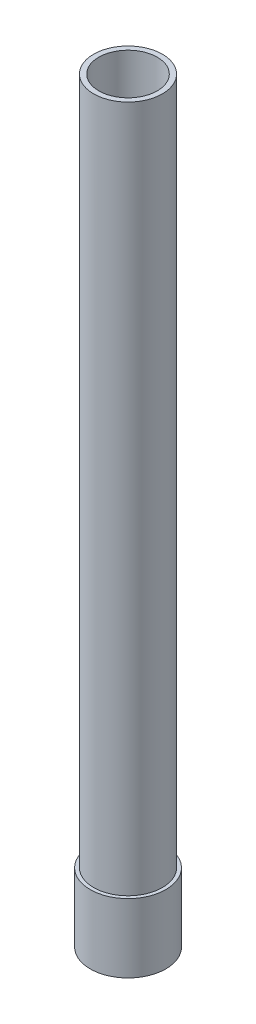
SolidWorks part; units mm, degrees
ref_plane "Front Plane" through (0, 0, 0) normal (0, 0, 1) x (1, 0, 0)
ref_plane "Top Plane" through (0, 0, 0) normal (0, 1, 0) x (1, 0, 0)
ref_plane "Right Plane" through (0, 0, 0) normal (1, 0, 0) x (0, 0, -1)
sketch "Sketch1" plane through (0, 0, 0) normal (0, 1, 0) x (1, 0, 0)
  circle A0 centre (0, 0) radius 10
  dimension "D1" = 20
extrude "Boss-Extrude1" add sketch "Sketch1" along normal blind 200
shell "Shell1" thickness 1.5
sketch "Sketch2" plane through (0, 0, 0) normal (0, -1, 0) x (1, 0, 0)
  circle A0 centre (0, 0) radius 11
  dimension "D1" = 22
extrude "Boss-Extrude2" add sketch "Sketch2" along normal blind 20
shell "Shell2" thickness 1.5
